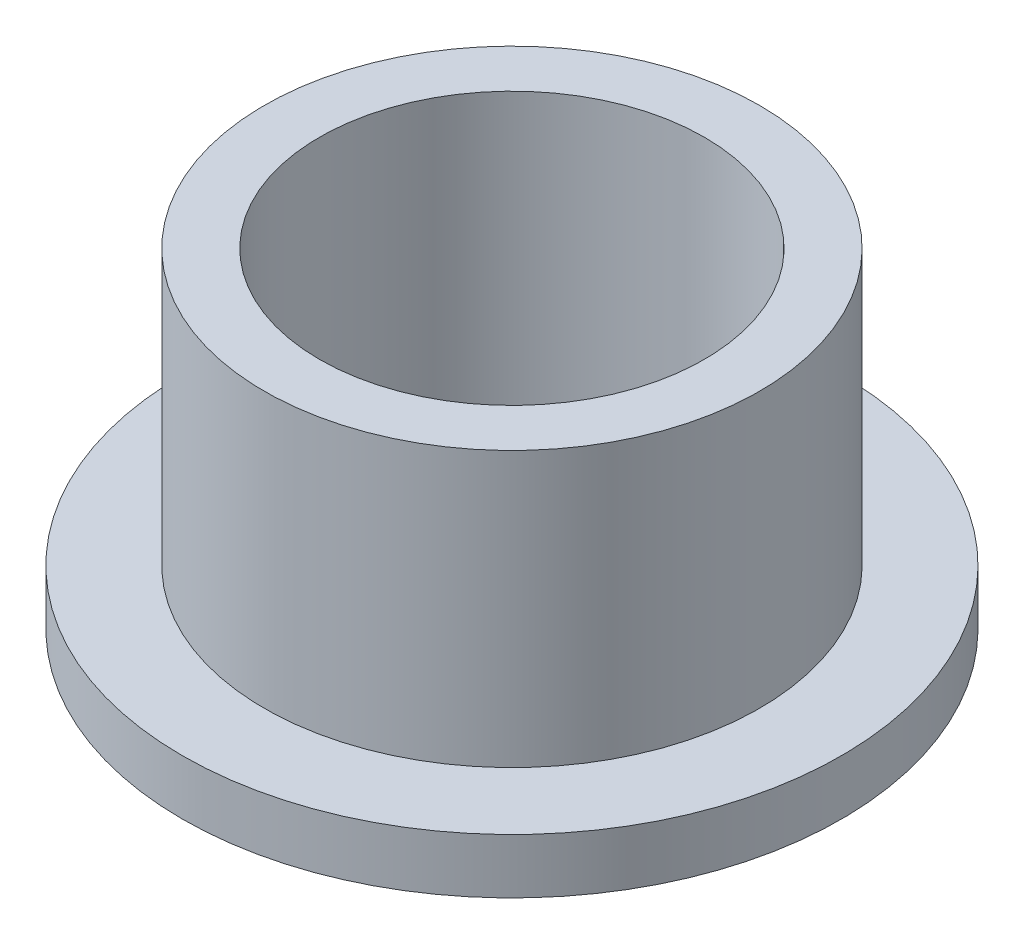
SolidWorks part; units mm, degrees
material "Brass"
ref_plane "Front" through (0, 0, 0) normal (0, 0, 1) x (1, 0, 0)
ref_plane "Top" through (0, 0, 0) normal (0, 1, 0) x (1, 0, 0)
ref_plane "Right" through (0, 0, 0) normal (1, 0, 0) x (0, 0, -1)
sketch "Sketch1" plane through (0, 0, 0) normal (0, 1, 0) x (1, 0, 0)
  circle A0 centre (0, 0) radius 11.1252
  circle A1 centre (0, 0) radius 14.3129
  circle A2 centre (0, 0) radius 19.05
  dimension "ID" = 22.2504
  dimension "OD" = 28.6258
  dimension "FlangeOD" = 38.1
sketch "Sketch2" plane through (0, 0, 0) normal (0, 1, 0) x (1, 0, 0)
  circle A0 centre (0, 0) radius 11.1252 construction
  circle A1 centre (0, 0) radius 14.3129 construction
  circle A2 centre (0, 0) radius 11.1252
  circle A3 centre (0, 0) radius 14.3129
extrude "Boss-Extrude1" add sketch "Sketch2" along normal blind 19.05
sketch "Sketch3" plane through (0, 0, 0) normal (0, 1, 0) x (1, 0, 0)
  circle A0 centre (0, 0) radius 19.05 construction
  circle A1 centre (0, 0) radius 14.3129 construction
  circle A2 centre (0, 0) radius 19.05
  circle A3 centre (0, 0) radius 14.3129
extrude "Boss-Extrude2" add sketch "Sketch3" along normal blind 3.175
